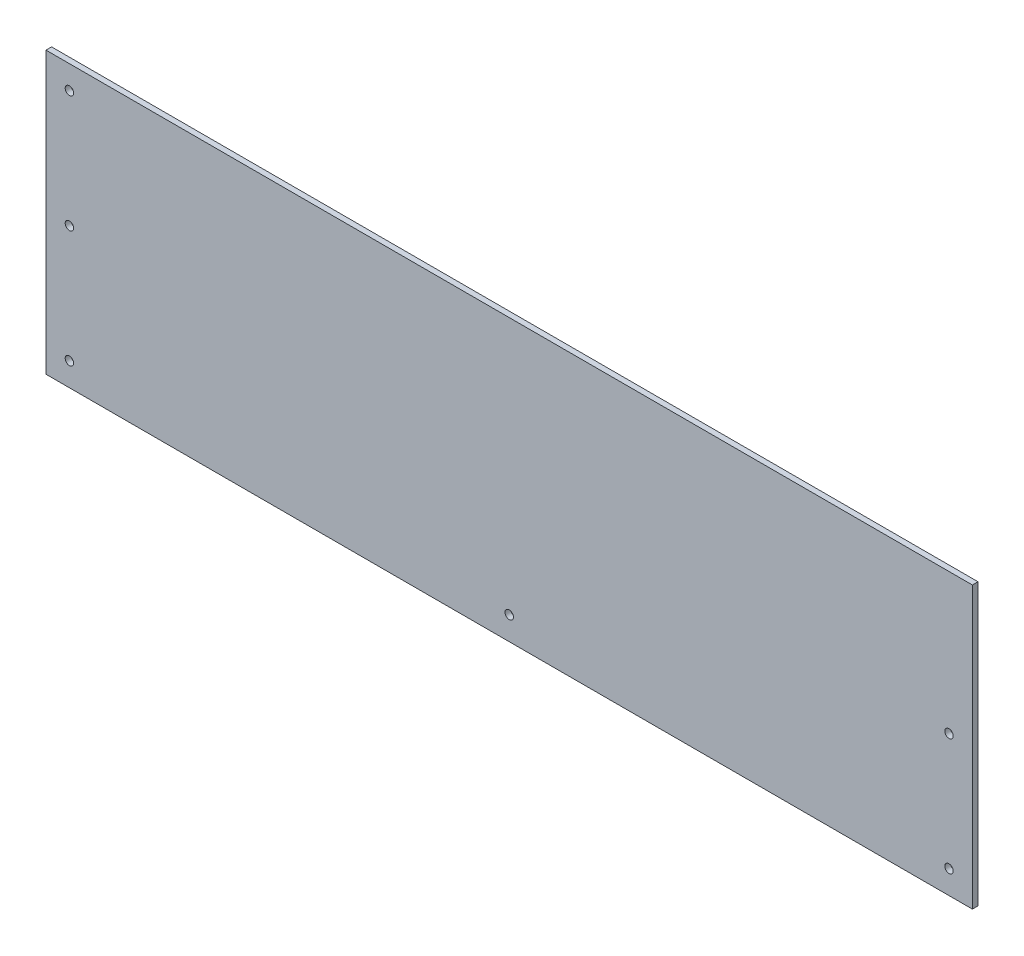
SolidWorks part; units mm, degrees
material "Acrylic (Medium-high impact)"
ref_plane "Front Plane" through (0, 0, 0) normal (0, 0, 1) x (1, 0, 0)
ref_plane "Top Plane" through (0, 0, 0) normal (0, 1, 0) x (1, 0, 0)
ref_plane "Right Plane" through (0, 0, 0) normal (1, 0, 0) x (0, 0, -1)
sketch "Sketch1" plane through (0, 0, 0) normal (0, 0, 1) x (1, 0, 0)
  line L1 (0, 0) -> (495, 0)
  line L2 (0, 0) -> (0, 150)
  line L3 (0, 150) -> (495, 150)
  line L4 (495, 0) -> (495, 150)
  line L5 (495, 0) -> (495, 250) construction
  line L6 (16.82, 150) -> (23.0371, 150) construction
extrude "Boss-Extrude1" add sketch "Sketch1" along normal blind 3
hole_wizard "M4 Clearance Hole1" positions "Sketch2" profile "Sketch3" hole size "M4" standard "ANSI Metric" end condition through all
sketch "Sketch2" plane through (0, 0, 3) normal (0, 0, 1) x (1, 0, 0)
  line L1 (495, 150) -> (0, 150) construction
  line L2 (0, 150) -> (0, 0) construction
  line L3 (0, 0) -> (495, 0) construction
  line L4 (495, 0) -> (495, 150) construction
  point P0 (12.5, 75)
  point P2 (12.5, 137.5)
  point P4 (12.5, 12.5)
  point P6 (247.5, 12.5)
  point P10 (482.5, 12.5)
  point P12 (482.5, 75)
  point P14 (482.5, 237.5)
  point P40 (0, 75)
  point P42 (247.5, 0)
  dimension "D1" = 12.5
  dimension "D2" = 12.5
  dimension "D3" = 12.5
  dimension "D4" = 12.5
sketch "Sketch3" plane through (12.5, 75, 3) normal (1, 0, 0) x (0, -1, 0)
  line L0 (0, 0) -> (0, 3)
  line L1 (0, 3) -> (2.25, 3)
  line L2 (2.25, 3) -> (2.25, 0)
  line L5 (2.25, 0) -> (0, 0)
  line L11 (0, -6.35) -> (0, 107.95) construction
  dimension "Thru Hole Dia." = 4.5
  dimension "Thru Hole Depth" = 3
